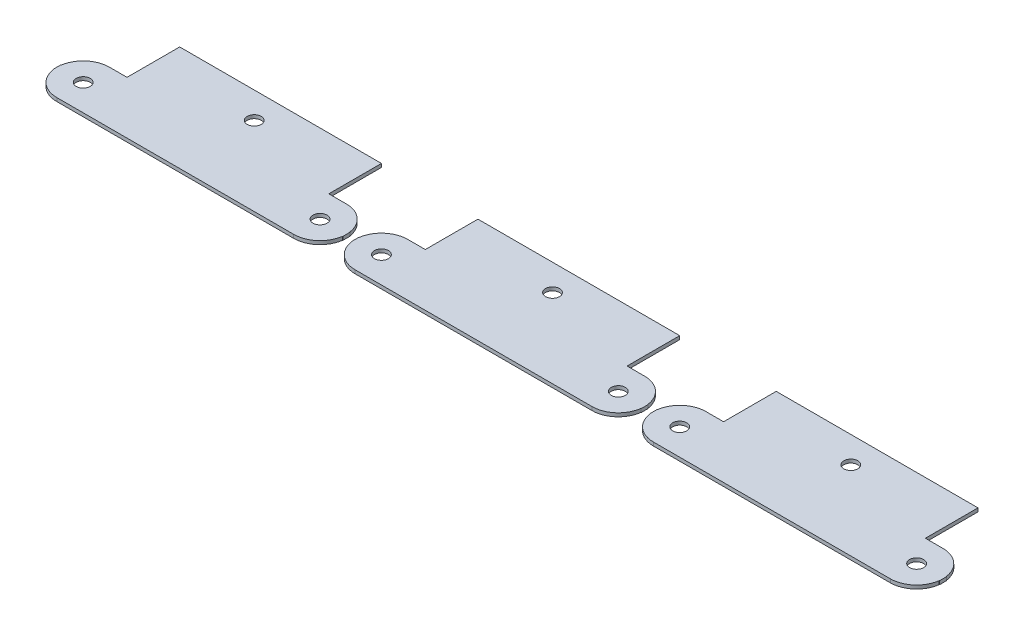
SolidWorks part; units mm, degrees
ref_plane "Front Plane" through (0, 0, 0) normal (0, 0, 1) x (1, 0, 0)
ref_plane "Top Plane" through (0, 0, 0) normal (0, 1, 0) x (1, 0, 0)
ref_plane "Right Plane" through (0, 0, 0) normal (1, 0, 0) x (0, 0, -1)
sketch "Sketch1" plane through (0, 0, 0) normal (0, 1, 0) x (1, 0, 0)
  line L0 (0, 0) -> (67.5, 0) construction
  line L1 (0, 7.5) -> (5, 7.5)
  line L2 (0, 7.5) -> (67.5, 7.5) construction
  line L3 (0, 7.5) -> (0, -7.5) construction
  line L4 (0, -7.5) -> (67.5, -7.5)
  line L5 (67.5, 7.5) -> (67.5, -7.5) construction
  line L6 (0, 7.5) -> (67.5, -7.5) construction
  line L7 (0, -7.5) -> (67.5, 7.5) construction
  line L8 (5, 7.5) -> (5, 22.5)
  line L9 (5, 22.5) -> (62.5, 22.5)
  line L10 (62.5, 22.5) -> (62.5, 7.5)
  line L11 (62.5, 7.5) -> (67.5, 7.5)
  line L12 (33.75, 0) -> (33.75, 22.5) construction
  line L13 (74.933, 1) -> (75, 1)
  line L14 (75, 1) -> (75, -1)
  line L15 (75, -1) -> (74.933, -1)
  line L17 (67.5, 0) -> (75, 0) construction
  line L32 (-7.5, 1) -> (-7.5, -1)
  line L33 (-7.5, -1) -> (-7.433, -1)
  line L44 (-7.5, 1) -> (-7.433, 1)
  circle A0 centre (0, 0) radius 2
  circle A1 centre (67.5, 0) radius 2
  arc A2 (0, 7.5) -> (0, -7.5) centre (0, 0) ccw construction
  arc A3 (67.5, -7.5) -> (67.5, 7.5) centre (67.5, 0) ccw construction
  arc A5 (67.5, 7.5) -> (74.933, 1) centre (67.5, 0) cw
  arc A7 (74.933, -1) -> (67.5, -7.5) centre (67.5, 0) cw
  arc A8 (-7.433, 1) -> (0, 7.5) centre (0, 0) cw
  arc A9 (-7.433, -1) -> (0, -7.5) centre (0, 0) ccw
  circle A94 centre (33.75, 15) radius 2
  point P5 (33.75, 0)
  point P23 (-7.5, 0)
  dimension "D3" = 15
  dimension "D6" = 4
  dimension "D8" = 4
  dimension "D7" = 7.5
  dimension "D2" = 15
  dimension "D4" = 67.5
  dimension "D5" = 5
  dimension "D13" = 2
extrude "Boss-Extrude1" add sketch "Sketch1" along normal blind 1
pattern_linear "LPattern1" count 3 spacing 85 along (1, 0, 0) of bodies 101
